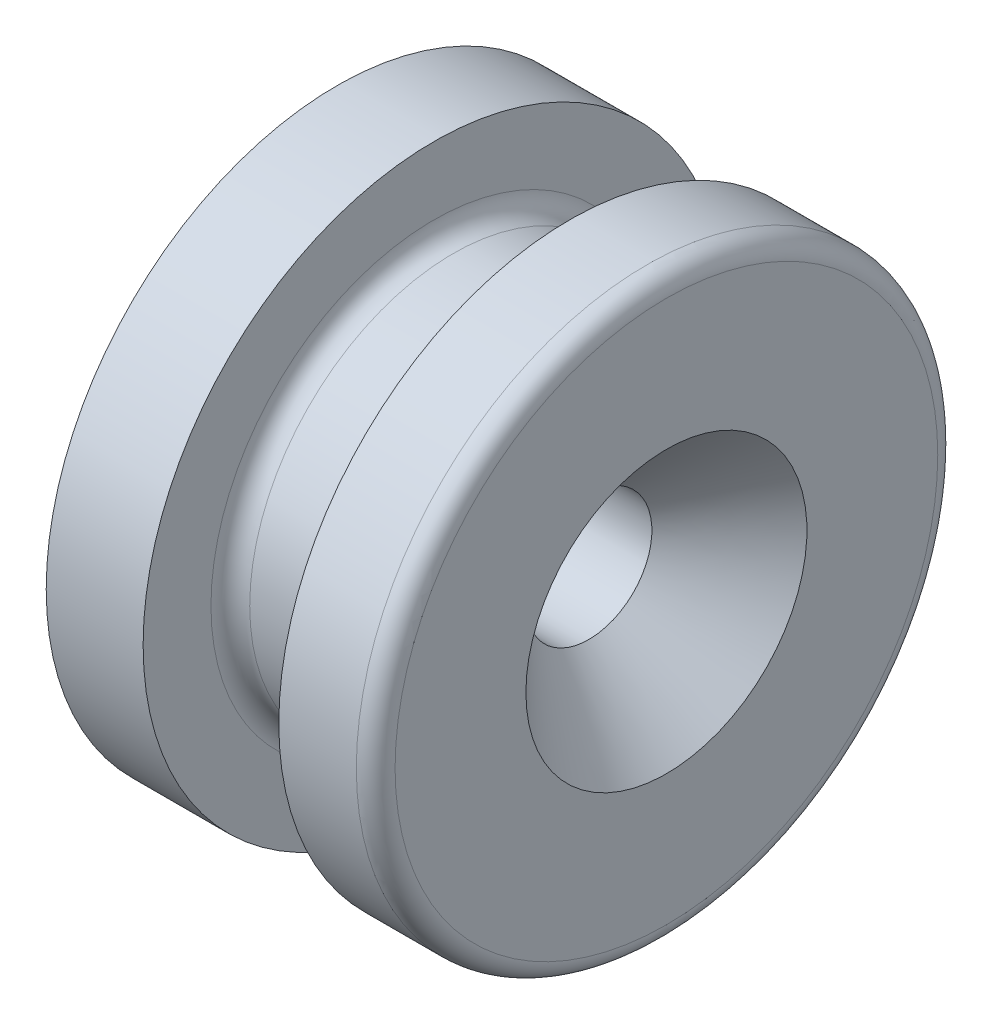
SolidWorks part; units mm, degrees
ref_plane "Ebene vorne" through (0, 0, 0) normal (0, 0, 1) x (1, 0, 0)
ref_plane "Ebene oben" through (0, 0, 0) normal (0, 1, 0) x (1, 0, 0)
ref_plane "Ebene rechts" through (0, 0, 0) normal (1, 0, 0) x (0, 0, -1)
sketch "Sketch1" plane through (0, 0, 0) normal (0, 0, 1) x (1, 0, 0)
  line L0 (-8.1219, 0) -> (30.7456, 0) construction
  line L1 (12, 15) -> (17, 15)
  line L3 (0, 3.25) -> (0, 15)
  line L4 (0, 15) -> (5, 15)
  line L5 (17, 3.25) -> (17, 15)
  line L6 (0, 3.25) -> (17, 3.25)
  line L7 (5, 15) -> (5, 10.5)
  line L8 (5, 10.5) -> (12, 10.5)
  line L9 (12, 15) -> (12, 10.5)
  point P1 (0, 0)
  point P6 (30.7456, 0)
  point P11 (14.5, 15)
  point P14 (-0.3186, 0)
  dimension "D1" = 21
  dimension "D2" = 7
  dimension "D3" = 17
  dimension "D4" = 30
  dimension "D5" = 6.5
revolve "Revolve1" add sketch "Sketch1" angle 360 about L0
fillet "Fillet1" radius 1 1 edges at (17, 0, 15)
fillet "Fillet2" radius 1 2 edges at (12, 0, 10.5) (5, 0, 10.5)
chamfer "Chamfer1" distance 4 angle 45 1 edges at (17, 0, 3.25)
